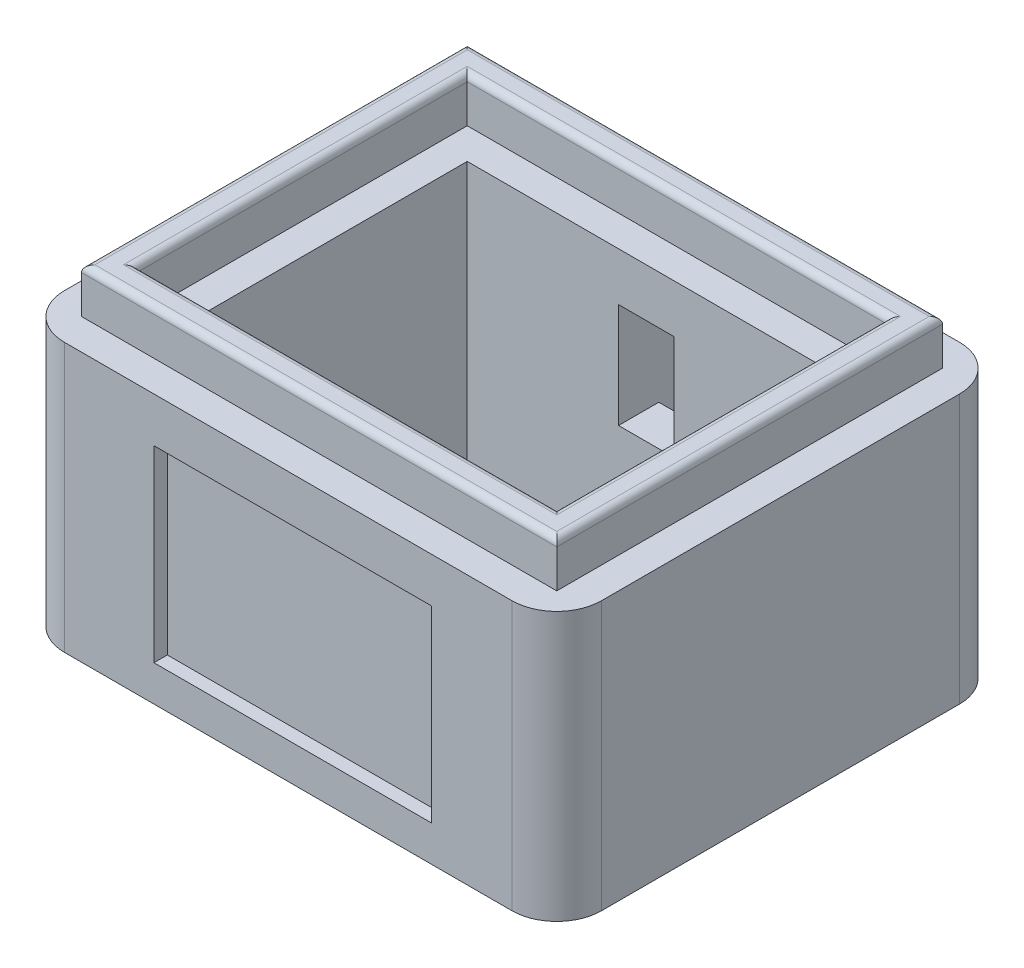
SolidWorks part; units mm, degrees
ref_plane "Front Plane" through (0, 0, 0) normal (0, 0, 1) x (1, 0, 0)
ref_plane "Top Plane" through (0, 0, 0) normal (0, 1, 0) x (1, 0, 0)
ref_plane "Right Plane" through (0, 0, 0) normal (1, 0, 0) x (0, 0, -1)
sketch "Sketch1" plane through (0, 0, 0) normal (0, 1, 0) x (1, 0, 0)
  line L1 (-60, 50) -> (60, 50)
  line L2 (-60, 50) -> (-60, -50)
  line L3 (-60, -50) -> (60, -50)
  line L4 (60, 50) -> (60, -50)
  point P4 (0, 0)
  dimension "D1" = 60
  dimension "D2" = 50
  dimension "D3" = 120
  dimension "D4" = 100
extrude "Boss-Extrude1" add sketch "Sketch1" along normal blind 50 and the other way blind 10
fillet "Fillet1" radius 10 4 edges at (60, 20, -50) (-60, 20, -50) (-60, 20, 50) (60, 20, 50)
sketch "Sketch2" plane through (0, 50, 0) normal (0, 1, 0) x (1, 0, 0)
  line L8 (40, -30) -> (40, 30)
  line L9 (40, 30) -> (-40, 30)
  line L10 (-40, 30) -> (-40, -30)
  line L11 (-40, -30) -> (40, -30)
  line L12 (40, -30) -> (40, 30)
  line L13 (40, 30) -> (-40, 30)
  line L14 (-40, 30) -> (-40, -30)
  line L15 (-40, -30) -> (40, -30)
  dimension "D1" = 20
extrude "Cut-Extrude1" cut sketch "Sketch2" against normal through all
sketch "Sketch3" plane through (0, -10, 0) normal (0, -1, 0) x (1, 0, 0)
  line L4 (53.1, 43.1) -> (-53.1, 43.1)
  line L5 (-53.1, 43.1) -> (-53.1, -43.1)
  line L6 (-53.1, -43.1) -> (53.1, -43.1)
  line L7 (53.1, -43.1) -> (53.1, 43.1)
  line L8 (-50, -40) -> (50, -40)
  line L9 (50, -40) -> (50, 40)
  line L10 (50, 40) -> (-50, 40)
  line L11 (-50, 40) -> (-50, -40)
  line L12 (-50, -40) -> (50, -40) construction
  line L13 (50, -40) -> (50, 40) construction
  line L14 (50, 40) -> (-50, 40) construction
  line L15 (-50, 40) -> (-50, -40) construction
  line L16 (46.9, 36.9) -> (-46.9, 36.9)
  line L17 (-46.9, 36.9) -> (-46.9, -36.9)
  line L18 (-46.9, -36.9) -> (46.9, -36.9)
  line L19 (46.9, -36.9) -> (46.9, 36.9)
  dimension "D1" = 10
  dimension "D2" = 3.1
  dimension "D3" = 3.1
extrude "Cut-Extrude2" cut sketch "Sketch3" against normal blind 10
sketch "Sketch4" plane through (0, 50, 0) normal (0, 1, 0) x (1, 0, 0)
  line L0 (-53.1, 43.1) -> (-53.1, -43.1)
  line L1 (-53.1, -43.1) -> (53.1, -43.1)
  line L2 (53.1, -43.1) -> (53.1, 43.1)
  line L3 (53.1, 43.1) -> (-53.1, 43.1)
  line L4 (-46.9, 36.9) -> (46.9, 36.9)
  line L5 (46.9, 36.9) -> (46.9, -36.9)
  line L6 (46.9, -36.9) -> (-46.9, -36.9)
  line L7 (-46.9, -36.9) -> (-46.9, 36.9)
extrude "Boss-Extrude2" add sketch "Sketch4" along normal blind 10
fillet "Fillet2" radius 1.5 8 edges at (46.9, 60, 0) (0, 60, -36.9) (-46.9, 60, 0) (0, 60, 36.9) (53.1, 60, 0) (0, 60, 43.1) (-53.1, 60, 0) (0, 60, -43.1)
sketch "Sketch5" plane through (0, 0, -50) normal (0, 0, -1) x (-1, 0, 0)
  line L0 (-50, 20) -> (50, 20) construction
  line L1 (-50, 50) -> (-50, -10) construction
  line L2 (50, -10) -> (50, 50) construction
  line L3 (0, 20) -> (0, 11) construction
  line L4 (6.2, 11) -> (-6.2, 11)
  line L5 (-6.2, 11) -> (-6.2, 44)
  line L6 (-6.2, 44) -> (6.2, 44)
  line L7 (0, 44) -> (0, 20) construction
  line L8 (6.2, 11) -> (6.2, 44)
  point P6 (0, 20)
  dimension "D1" = 33
  dimension "D2" = 6.2
  dimension "D3" = 24
extrude "Cut-Extrude3" cut sketch "Sketch5" against normal blind 11
sketch "Sketch9" plane through (0, 0, -50) normal (0, 0, -1) x (-1, 0, 0)
  line L1 (-6.2, 27.5) -> (-6.2, 39.2)
  line L7 (-6.2, 11) -> (-6.2, 44) construction
  line L8 (-6.2, 39.2) -> (6.2, 39.2)
  line L9 (6.2, 11) -> (6.2, 44) construction
  line L10 (6.2, 39.2) -> (6.2, 15.8)
  line L11 (6.2, 15.8) -> (-6.2, 15.8)
  line L12 (-6.2, 15.8) -> (-6.2, 27.5)
  dimension "D1" = 11.7
sketch "Sketch10" plane through (0, 0, 50) normal (0, 0, 1) x (1, 0, 0)
  line L0 (-50, 50) -> (-50, -10) construction
  line L1 (50, -10) -> (50, 50) construction
  line L2 (-50, 20) -> (50, 20) construction
  line L4 (-30, 40) -> (32, 40)
  line L5 (-30, 40) -> (-30, -2)
  line L6 (-30, -2) -> (32, -2)
  line L7 (32, 40) -> (32, -2)
  point P0 (-50, 20)
  point P1 (50, 20)
  point P8 (0, 20)
  dimension "D1" = 30
  dimension "D2" = 62
  dimension "D3" = 20
  dimension "D4" = 42
extrude "Cut-Extrude7" cut sketch "Sketch10" against normal blind 3
sketch "Sketch12" plane through (0, 50, 0) normal (0, 1, 0) x (1, 0, 0)
  line L0 (50, 50) -> (50, 60)
  line L1 (50, 60) -> (40, 60)
  line L2 (40, 60) -> (40, 55)
  line L3 (40, 55) -> (45, 55)
  line L4 (45, 55) -> (45, 50)
  line L5 (50, 50) -> (-50, 50) construction
  line L6 (45, 50) -> (50, 50)
  line L7 (0, 50) -> (0, 76.8724) construction
  line L8 (-50, 50) -> (-50, 60)
  line L9 (-45, 50) -> (-50, 50)
  line L10 (-45, 55) -> (-45, 50)
  line L11 (-40, 55) -> (-45, 55)
  line L12 (-40, 60) -> (-40, 55)
  line L13 (-50, 60) -> (-40, 60)
  dimension "D1" = 10
  dimension "D2" = 5
  dimension "D3" = 5
  dimension "D4" = 10
extrude "Boss-Extrude3" [suppressed] add sketch "Sketch12" against normal up to surface (60 mm away)
fillet "Fillet3" [suppressed] radius 5
extrude "Cut-Extrude8" cut sketch "Sketch9" against normal up to surface (20 mm away) up to face at (0, 20, -30)
equation "\"X\"=120"
equation "\"D3@Sketch1\"=\"X\""
equation "\"Y\"=100"
equation "\"D4@Sketch1\"=\"Y\""
equation "\"Z\"= 60"
equation "\"D1@Boss-Extrude1\"=\"Z\"-10"
